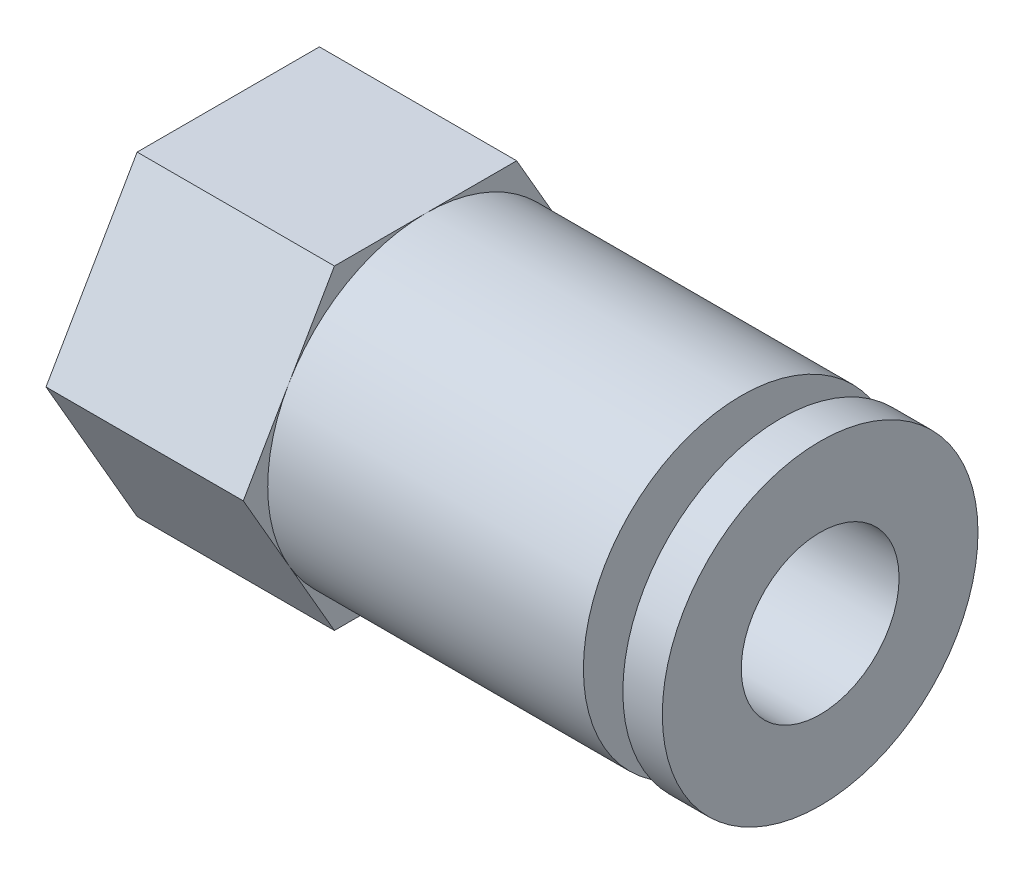
SolidWorks part; units mm, degrees
ref_plane "前视基准面" through (0, 0, 0) normal (0, 0, 1) x (1, 0, 0)
ref_plane "上视基准面" through (0, 0, 0) normal (0, 1, 0) x (1, 0, 0)
ref_plane "右视基准面" through (0, 0, 0) normal (1, 0, 0) x (0, 0, -1)
sketch "草图1" plane through (0, 0, 0) normal (1, 0, 0) x (0, 0, -1)
  line L1 (-2.3094, 4) -> (-4.6188, 0)
  line L2 (-4.6188, 0) -> (-2.3094, -4)
  line L3 (-2.3094, -4) -> (2.3094, -4)
  line L4 (2.3094, -4) -> (4.6188, 0)
  line L5 (4.6188, 0) -> (2.3094, 4)
  line L6 (2.3094, 4) -> (-2.3094, 4)
  circle A0 centre (0, 0) radius 4 construction
  dimension "D1" = 8
extrude "凸台-拉伸1" add sketch "草图1" along normal blind 5
sketch "草图2" plane through (5, 0, 0) normal (1, 0, 0) x (0, 0, -1)
  circle A0 centre (0, 0) radius 4
  dimension "D1" = 8
extrude "凸台-拉伸2" add sketch "草图2" along normal blind 8
sketch "草图3" plane through (13, 0, 0) normal (1, 0, 0) x (0, 0, -1)
  circle A0 centre (0, 0) radius 2.5
  dimension "D1" = 5
extrude "凸台-拉伸3" add sketch "草图3" along normal blind 1
sketch "草图4" plane through (14, 0, 0) normal (1, 0, 0) x (0, 0, -1)
  circle A0 centre (0, 0) radius 4
  dimension "D1" = 8
extrude "凸台-拉伸4" add sketch "草图4" along normal blind 1
sketch "草图5" plane through (15, 0, 0) normal (1, 0, 0) x (0, 0, -1)
  circle A0 centre (0, 0) radius 2
  dimension "D1" = 4
extrude "切除-拉伸1" cut sketch "草图5" against normal through all
